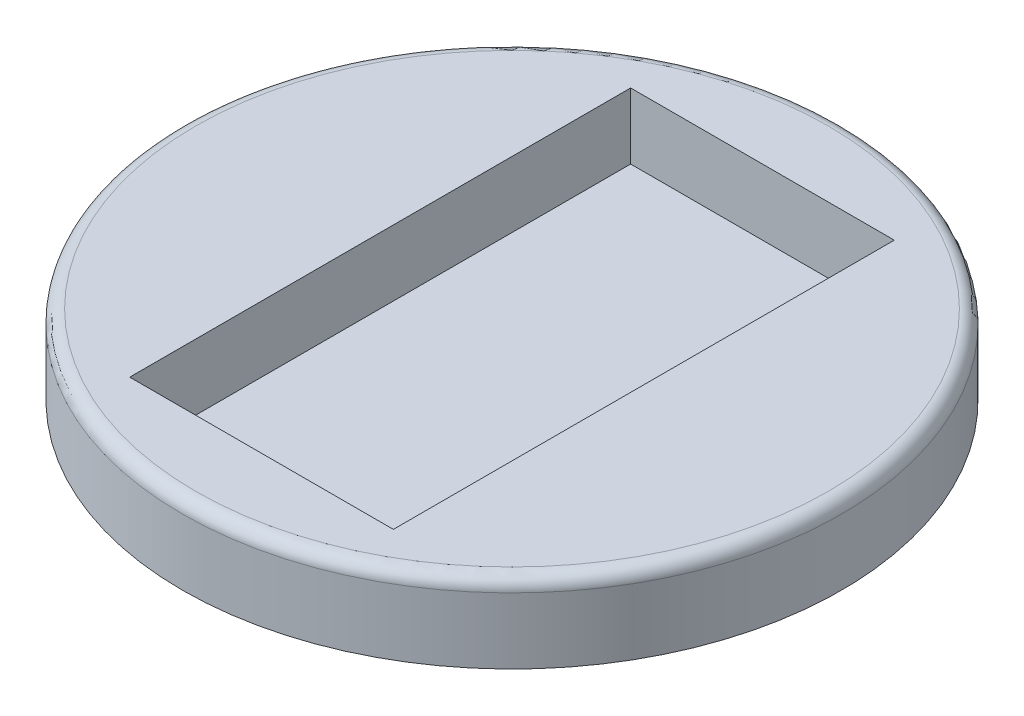
SolidWorks part; units mm, degrees
ref_plane "Front Plane" through (0, 0, 0) normal (0, 0, 1) x (1, 0, 0)
ref_plane "Top Plane" through (0, 0, 0) normal (0, 1, 0) x (1, 0, 0)
ref_plane "Right Plane" through (0, 0, 0) normal (1, 0, 0) x (0, 0, -1)
sketch "Sketch1" plane through (0, 0, 0) normal (0, 1, 0) x (1, 0, 0)
  circle A0 centre (0, 0) radius 25
  circle A1 centre (0, 0) radius 23.25 construction
  dimension "D1" = 50
  dimension "D2" = 1.75
extrude "Boss-Extrude1" add sketch "Sketch1" along normal blind 6
sketch "Sketch2" plane through (0, 6, 0) normal (0, 1, 0) x (1, 0, 0)
  line L1 (-10, 19) -> (10, 19)
  line L2 (-10, 19) -> (-10, -19)
  line L3 (-10, -19) -> (10, -19)
  line L4 (10, 19) -> (10, -19)
  line L5 (-10, 19) -> (10, -19) construction
  line L6 (-10, -19) -> (10, 19) construction
  point P0 (0, 0)
  dimension "D1" = 38
  dimension "D2" = 20
extrude "Cut-Extrude1" cut sketch "Sketch2" against normal blind 5
fillet "Fillet1" radius 1 1 edges at (0, 6, 25)
